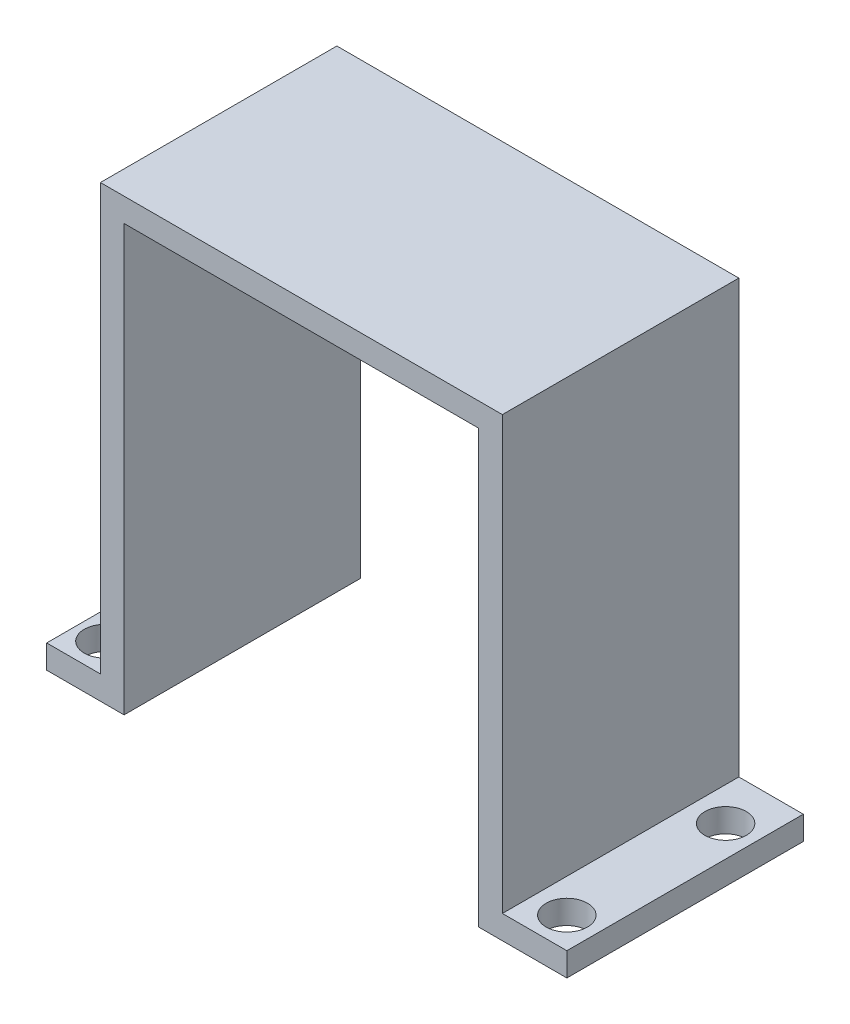
SolidWorks part; units mm, degrees
ref_plane "Plano frontal" through (0, 0, 0) normal (0, 0, 1) x (1, 0, 0)
ref_plane "Plano superior" through (0, 0, 0) normal (0, 1, 0) x (1, 0, 0)
ref_plane "Plano direito" through (0, 0, 0) normal (1, 0, 0) x (0, 0, -1)
sketch "Esboço1" plane through (0, 0, 0) normal (0, 0, 1) x (1, 0, 0)
  line L0 (-29.2021, -18.4545) -> (-29.2021, -16.4545)
  line L1 (-29.2021, -16.4545) -> (-24.6566, -16.4545)
  line L2 (-24.6566, -16.4545) -> (-24.6566, 19.5455)
  line L3 (-24.6566, 19.5455) -> (9.3434, 19.5455)
  line L8 (7.3434, -19) -> (7.3434, 17.5455)
  line L9 (7.3434, 17.5455) -> (-22.6566, 17.5455)
  line L10 (-22.6566, 17.5455) -> (-22.6566, -16.4545)
  line L11 (-22.6566, -16.4545) -> (-22.6566, -18.4545)
  line L12 (-22.6566, -18.4545) -> (-29.2021, -18.4545)
  line L13 (9.3434, 19.5455) -> (9.3434, -17)
  line L14 (9.3434, -17) -> (14.7979, -17)
  line L15 (14.7979, -17) -> (14.7979, -19)
  line L16 (14.7979, -19) -> (7.3434, -19)
  point P8 (12.0706, -17)
  dimension "D1" = 34
  dimension "D2" = 2
  dimension "D3" = 30
  dimension "D4" = 36
  dimension "D5" = 2
  dimension "D6" = 2
  dimension "D7" = 2
extrude "Ressalto-extrusão1" add sketch "Esboço1" along normal blind 20 contours L10 L11 L12 L0 L1 L2 L3 L13 L14 L15 L16 L8 L9
hole_wizard "Broca de rosquear para helicoide M31" positions "Esboço2" profile "Esboço3" hole size "M3x0.5" standard "Ansi Metric"
sketch "Esboço2" plane through (0, -17, 0) normal (0, 1, 0) x (1, 0, 0)
  point P0 (12.1898, -3.9652)
  point P2 (12.1898, -17.3969)
  point P4 (-26.6332, -3.9652)
  point P6 (-26.6332, -17.3969)
sketch "Esboço3" plane through (12.1898, -17, 3.9652) normal (1, 0, 0) x (0, 0, 1)
  line L0 (0, 0) -> (0, 11.0515)
  line L1 (0, 11.0515) -> (1.75, 10)
  line L2 (1.75, 10) -> (1.75, 0)
  line L5 (1.75, 0) -> (0, 0)
  line L10 (0, 11.0515) -> (-1.75, 10) construction
  line L11 (0, -6.35) -> (0, 107.95) construction
  dimension "Hole Dia." = 3.5
  dimension "Hole Depth" = 10
  dimension "Drill Angle" = 118
hole_wizard "Broca de rosquear para helicoide M32" positions "Esboço4" profile "Esboço5" hole size "M3x0.5" standard "Ansi Metric"
sketch "Esboço4" plane through (0, -16.4545, 0) normal (0, 1, 0) x (1, 0, 0)
  point P2 (-26.8644, -17.4113)
  point P4 (-26.8644, -4.2288)
  point P7 (0, 0)
sketch "Esboço5" plane through (-26.8644, -16.4545, 17.4113) normal (1, 0, 0) x (0, 0, 1)
  line L0 (0, 0) -> (0, 11.0515)
  line L1 (0, 11.0515) -> (1.75, 10)
  line L2 (1.75, 10) -> (1.75, 0)
  line L5 (1.75, 0) -> (0, 0)
  line L10 (0, 11.0515) -> (-1.75, 10) construction
  line L11 (0, -6.35) -> (0, 107.95) construction
  dimension "Hole Dia." = 3.5
  dimension "Hole Depth" = 10
  dimension "Drill Angle" = 118
